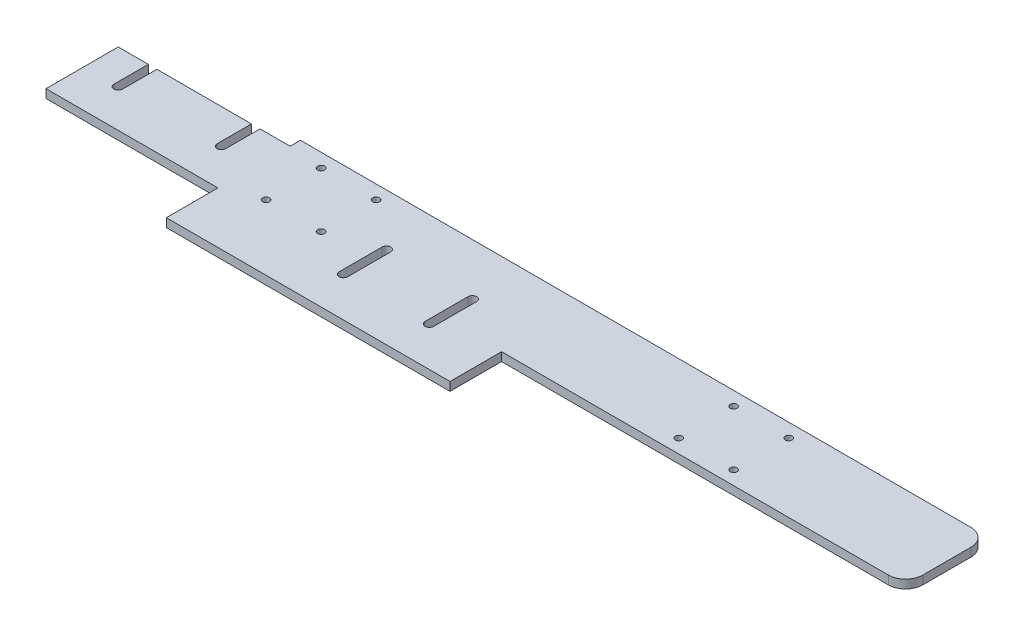
SolidWorks part; units mm, degrees
material "PMMA"
ref_plane "前视基准面" through (0, 0, 0) normal (0, 0, 1) x (1, 0, 0)
ref_plane "上视基准面" through (0, 0, 0) normal (0, 1, 0) x (1, 0, 0)
ref_plane "右视基准面" through (0, 0, 0) normal (1, 0, 0) x (0, 0, -1)
sketch "Sketch1" plane through (0, 0, 0) normal (0, 1, 0) x (1, 0, 0)
  line L0 (0, 0) -> (0, -48)
  line L1 (0, -48) -> (400, -48)
  line L2 (400, -48) -> (400, 0)
  line L3 (400, 0) -> (0, 0)
  line L4 (-43.9692, -24) -> (451.1153, -24) construction
  line L5 (20, 40.7588) -> (20, -88.7642) construction
  line L6 (-43.9692, -8) -> (451.1153, -8) construction
  line L7 (36, 40.7588) -> (36, -88.7642) construction
  line L8 (292, 17.2237) -> (292, -57.1638) construction
  line L9 (276, 17.2237) -> (276, -57.1638) construction
  circle A0 centre (20, -8) radius 2
  circle A1 centre (20, -40) radius 2
  circle A2 centre (292, -8) radius 2
  circle A3 centre (292, -40) radius 2
  circle A4 centre (52, -40) radius 2
  circle A5 centre (52, -8) radius 2
  circle A6 centre (260, -40) radius 2
  circle A7 centre (260, -8) radius 2
  dimension "D6" = 4
  dimension "D7" = 4
  dimension "D1" = 48
  dimension "D2" = 400
  dimension "D3" = 24
  dimension "D4" = 20
  dimension "D8" = 272
  dimension "D9" = 16
  dimension "D5" = 16
  dimension "D10" = 16
extrude "Boss-Extrude1" add sketch "Sketch1" along normal blind 5
sketch "Sketch3" plane through (0, 0, 0) normal (-1, 0, 0) x (0, 0, 1)
  line L0 (48, 5) -> (48, 0)
  line L1 (48, 0) -> (6, 0)
  line L2 (0, 0) -> (48, 0) construction
  line L3 (6, 0) -> (6, 5)
  line L4 (0, 5) -> (48, 5) construction
  line L5 (6, 5) -> (48, 5)
  dimension "D1" = 42
extrude "Boss-Extrude2" add sketch "Sketch3" along normal blind 100
sketch "Sketch5" plane through (0, 0, 48) normal (0, 0, 1) x (1, 0, 0)
  line L0 (0, 0) -> (0, 5)
  line L1 (-100, 5) -> (400, 5) construction
  line L2 (0, 5) -> (165, 5)
  line L3 (165, 5) -> (165, 0)
  line L4 (-100, 0) -> (400, 0) construction
  line L5 (165, 0) -> (0, 0)
  dimension "D1" = 165
extrude "Boss-Extrude3" add sketch "Sketch5" along normal blind 30
sketch "Sketch4" plane through (0, 5, 0) normal (0, 1, 0) x (1, 0, 0)
  line L0 (-80, -6) -> (-80, -26) construction
  line L1 (-77.5, -6) -> (-77.5, -26)
  line L2 (-82.5, -6) -> (-82.5, -26)
  line L3 (-20, -6) -> (-20, -26) construction
  line L4 (-17.5, -6) -> (-17.5, -26)
  line L5 (-22.5, -6) -> (-22.5, -26)
  line L6 (-100, -6) -> (0, -6) construction
  line L8 (-100, -48) -> (-100, -6) construction
  line L9 (80, -30) -> (80, -55) construction
  line L10 (82.5, -30) -> (82.5, -55)
  line L11 (77.5, -30) -> (77.5, -55)
  line L12 (400, 0) -> (0, 0) construction
  line L13 (0, 0) -> (0, -6) construction
  line L14 (130, -30) -> (130, -55) construction
  line L15 (132.5, -30) -> (132.5, -55)
  line L16 (127.5, -30) -> (127.5, -55)
  arc A0 (-77.5, -6) -> (-82.5, -6) centre (-80, -6) ccw
  arc A1 (-82.5, -26) -> (-77.5, -26) centre (-80, -26) ccw
  arc A2 (-17.5, -6) -> (-22.5, -6) centre (-20, -6) ccw
  arc A3 (-22.5, -26) -> (-17.5, -26) centre (-20, -26) ccw
  arc A4 (82.5, -30) -> (77.5, -30) centre (80, -30) ccw
  arc A5 (77.5, -55) -> (82.5, -55) centre (80, -55) ccw
  arc A6 (132.5, -30) -> (127.5, -30) centre (130, -30) ccw
  arc A7 (127.5, -55) -> (132.5, -55) centre (130, -55) ccw
  point P2 (-80, -16)
  point P7 (-20, -16)
  point P16 (80, -42.5)
  point P31 (130, -42.5)
  dimension "D1" = 2.5
  dimension "D2" = 2.5
  dimension "D9" = 2.5
  dimension "D3" = 20
  dimension "D4" = 20
  dimension "D5" = 0
  dimension "D6" = 20
  dimension "D7" = 0
  dimension "D8" = 60
  dimension "D10" = 25
  dimension "D11" = 30
  dimension "D12" = 80
  dimension "D14" = 50
  dimension "D13" = 2
extrude "Cut-Extrude1" cut sketch "Sketch4" against normal through all
fillet "Fillet1" radius 10 2 edges at (400, 2.5, 48) (400, 2.5, 0)
